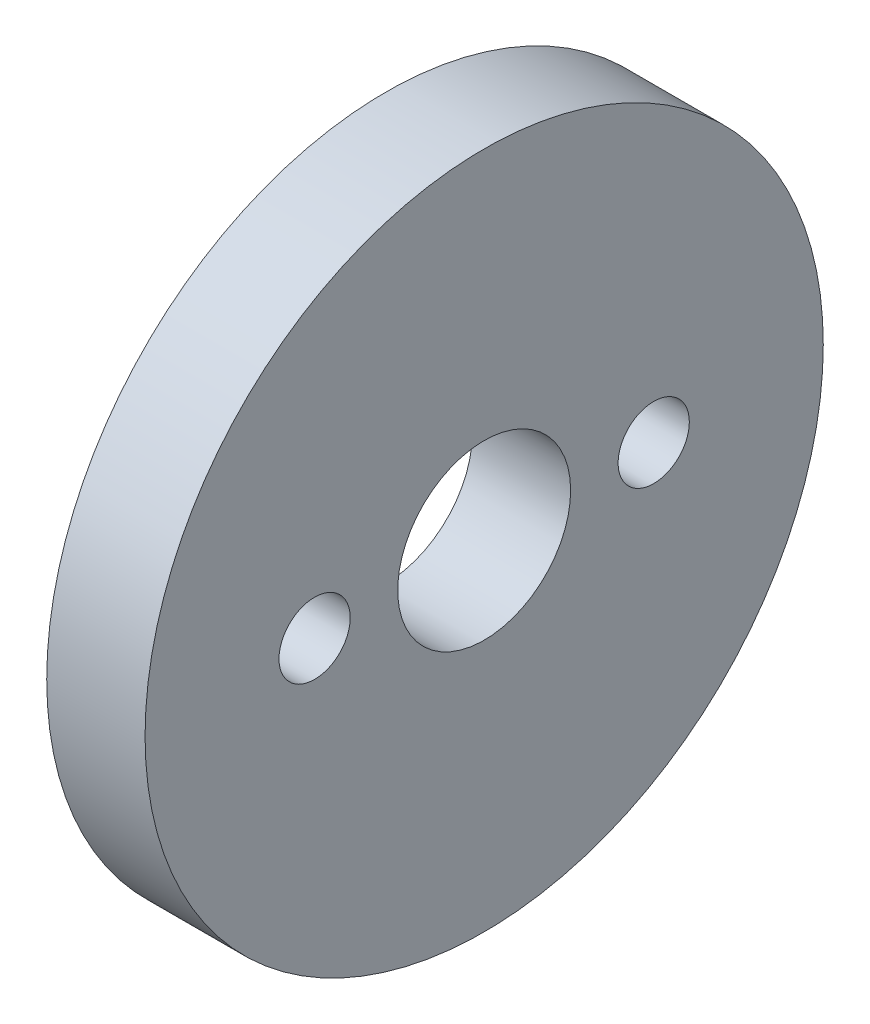
SolidWorks part; units mm, degrees
material "ナイロン"
ref_plane "正面" through (0, 0, 0) normal (0, 0, 1) x (1, 0, 0)
ref_plane "平面" through (0, 0, 0) normal (0, 1, 0) x (1, 0, 0)
ref_plane "右側面" through (0, 0, 0) normal (1, 0, 0) x (0, 0, -1)
sketch "ｽｹｯﾁ1" plane through (0, 0, 0) normal (1, 0, 0) x (0, 0, -1)
  circle A0 centre (0, 0) radius 20
  dimension "D1" = 40
extrude "ﾎﾞｽ - 押し出し1" add sketch "ｽｹｯﾁ1" along normal blind 5.8
sketch "ｽｹｯﾁ2" plane through (5.8, 0, 0) normal (1, 0, 0) x (0, 0, -1)
  line L0 (0, 0) -> (50000, 0) construction
  line L1 (0, 0) -> (0, 50000) construction
  circle A0 centre (10, 0) radius 2.1
  circle A1 centre (-10, 0) radius 2.1
  circle A2 centre (0, 0) radius 5.1
  dimension "D1" = 20
  dimension "D2" = 4.2
  dimension "D3" = 10.2
extrude "ｶｯﾄ - 押し出し1" cut sketch "ｽｹｯﾁ2" against normal through all
